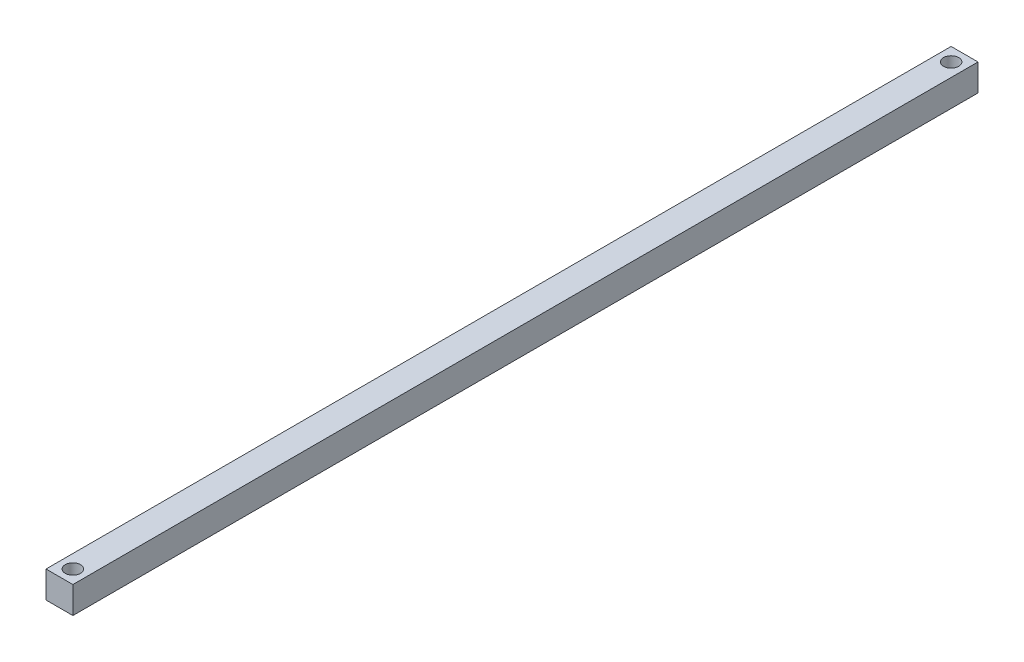
SolidWorks part; units mm, degrees
ref_plane "Ön Düzlem" through (0, 0, 0) normal (0, 0, 1) x (1, 0, 0)
ref_plane "Üst Düzlem" through (0, 0, 0) normal (0, 1, 0) x (1, 0, 0)
ref_plane "Sağ Düzlem" through (0, 0, 0) normal (1, 0, 0) x (0, 0, -1)
sketch "Sketch1" plane through (0, 0, 0) normal (0, 0, 1) x (1, 0, 0)
  line L1 (-7.5, -7.5) -> (7.5, -7.5)
  line L2 (-7.5, -7.5) -> (-7.5, 7.5)
  line L3 (-7.5, 7.5) -> (7.5, 7.5)
  line L4 (7.5, -7.5) -> (7.5, 7.5)
  line L5 (-7.5, -7.5) -> (7.5, 7.5) construction
  line L6 (-7.5, 7.5) -> (7.5, -7.5) construction
  point P0 (0, 0)
  dimension "D1" = 15
extrude "Boss-Extrude1" add sketch "Sketch1" along normal mid plane 505
hole_wizard "Hole2" positions "Sketch7" profile "Sketch8" legacy
sketch "Sketch7" plane through (0, -7.5, 0) normal (0, -1, 0) x (-1, 0, 0)
  line L0 (7.5, 252.5) -> (-7.5, 252.5) construction
  point P0 (0, 245)
  dimension "D1" = 7.5
sketch "Sketch8" plane through (0, -7.5, -245) normal (1, 0, 0) x (0, 0, -1)
  line L0 (0, 0) -> (0, 15)
  line L1 (0, 15) -> (4.25, 15)
  line L2 (4.25, 15) -> (4.25, 8)
  line L3 (4.25, 8) -> (7, 8)
  line L4 (7, 8) -> (7, 0)
  line L5 (7, 0) -> (0, 0)
  line L6 (0, 110) -> (0, -10) construction
  dimension "Diameter" = 8.5
  dimension "Depth" = 15
  dimension "C-Bore Diameter" = 14
  dimension "C-Bore Depth" = 8
mirror "Mirror1" about plane through (0, 0, 0) normal (0, 0, 1) of "Hole2"
